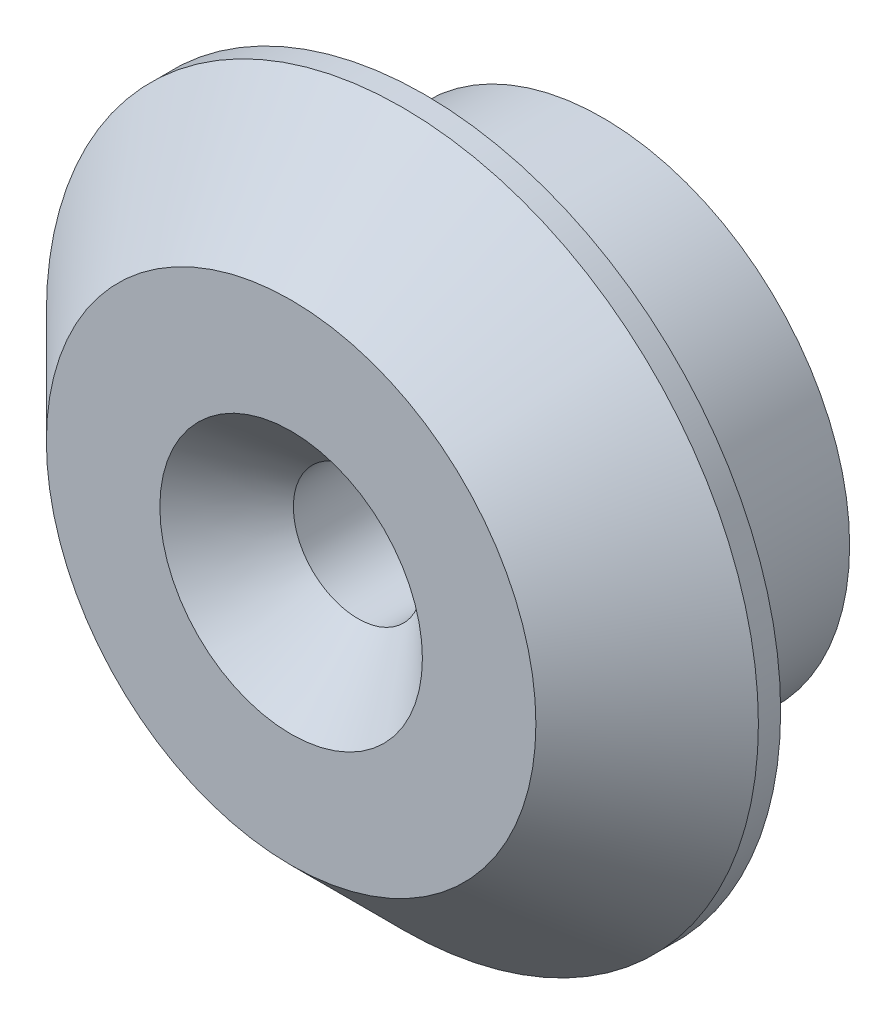
SolidWorks part; units mm, degrees
ref_plane "Alzado" through (0, 0, 0) normal (0, 0, 1) x (1, 0, 0)
ref_plane "Planta" through (0, 0, 0) normal (0, 1, 0) x (1, 0, 0)
ref_plane "Vista lateral" through (0, 0, 0) normal (1, 0, 0) x (0, 0, -1)
sketch "Croquis1" plane through (0, 0, 0) normal (0, 0, 1) x (1, 0, 0)
  circle A0 centre (0, 0) radius 5.55
  circle A1 centre (0, 0) radius 1.45
  circle A2 centre (0, 0) radius 1.45 construction
  circle A3 centre (0, 0) radius 5.55 construction
extrude "Saliente-Extruir1" add sketch "Croquis1" along normal blind 7
chamfer "Chaflán1" distance 1.5 angle 45 1 edges at (1.45, 0, 7)
sketch "Croquis2" plane through (0, 0, 4) normal (0, 0, 1) x (1, 0, 0)
  circle A0 centre (0, 0) radius 8
  circle A1 centre (0, 0) radius 5.55
  circle A2 centre (0, 0) radius 5.55 construction
  dimension "D1" = 16
extrude "Saliente-Extruir2" add sketch "Croquis2" along normal blind 3
chamfer "Chaflán2" distance 2.5 angle 45 1 edges at (8, 0, 7)
